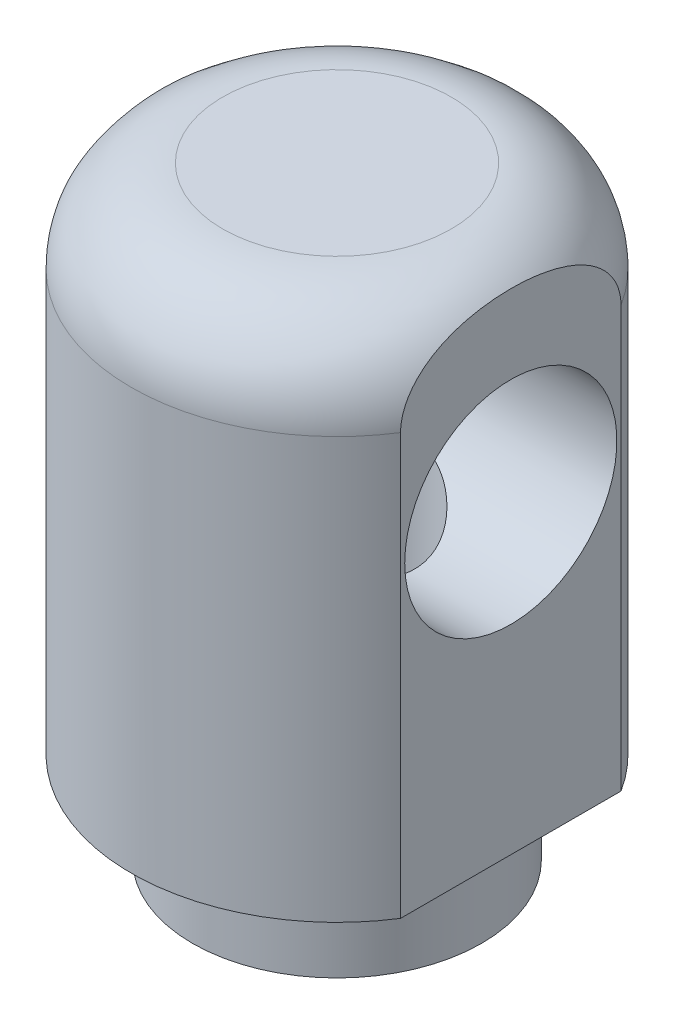
SolidWorks part; units mm, degrees
material "6061-T6 (SS)"
ref_plane "Front Plane" through (0, 0, 0) normal (0, 0, 1) x (1, 0, 0)
ref_plane "Top Plane" through (0, 0, 0) normal (0, 1, 0) x (1, 0, 0)
ref_plane "Right Plane" through (0, 0, 0) normal (1, 0, 0) x (0, 0, -1)
sketch "Sketch1" plane through (0, 0, 0) normal (0, 1, 0) x (1, 0, 0)
  circle A0 centre (0, 0) radius 11.25
  dimension "D1" = 22.5
extrude "Boss-Extrude1" add sketch "Sketch1" along normal blind 33
fillet "Fillet1" radius 5 1 edges at (0, 33, 11.25)
sketch "Sketch2" plane through (0, 33, 0) normal (0, 1, 0) x (1, 0, 0)
  line L0 (0, 11.25) -> (0, -11.25) construction
  line L1 (-9.5, 6.026) -> (-9.5, -6.026)
  line L2 (9.5, 6.026) -> (9.5, -6.026)
  circle A0 centre (0, 0) radius 11.25 construction
  arc A1 (-9.5, 6.026) -> (-9.5, -6.026) centre (0, 0) ccw
  arc A2 (9.5, -6.026) -> (9.5, 6.026) centre (0, 0) ccw
  dimension "D1" = 19
extrude "Cut-Extrude1" cut sketch "Sketch2" against normal through all
sketch "Sketch3" plane through (0, 0, 0) normal (0, -1, 0) x (1, 0, 0)
  circle A0 centre (0, 0) radius 7.9
  dimension "D1" = 15.8
extrude "Cut-Extrude2" cut sketch "Sketch3" against normal blind 5 flip side to cut
sketch "Sketch4" plane through (-9.5, 0, 0) normal (-1, 0, 0) x (0, 0, 1)
  line L0 (6.25, 33) -> (-6.25, 33) construction
  circle A0 centre (0, 21.7) radius 5.8
  dimension "D1" = 11.6
  dimension "D2" = 11.3
extrude "Cut-Extrude3" cut sketch "Sketch4" against normal through all
sketch "Sketch5" plane through (0, 0, 0) normal (0, -1, 0) x (1, 0, 0)
  circle A0 centre (0, 0) radius 4.25
  dimension "D1" = 8.5
extrude "Cut-Extrude4" cut sketch "Sketch5" against normal up to next
cosmetic thread "Cosmetic Thread1" parameters "D2"=10
